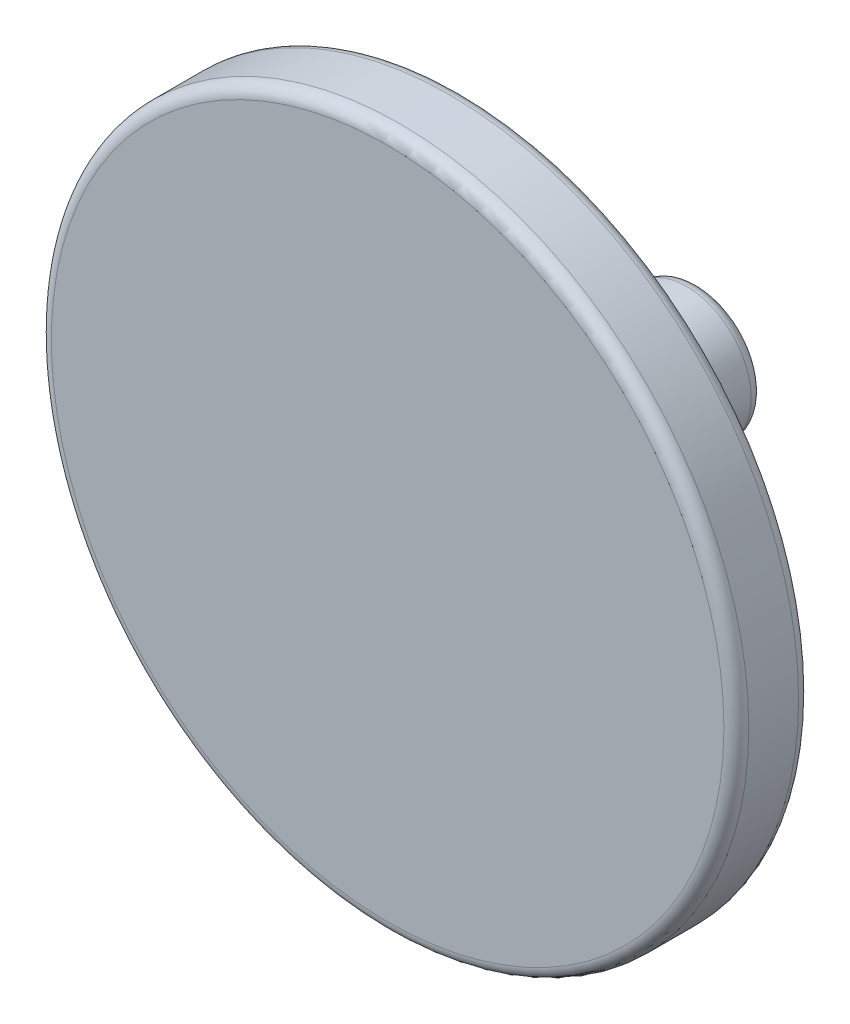
SolidWorks part; units mm, degrees
ref_plane "Front Plane" through (0, 0, 0) normal (0, 0, 1) x (1, 0, 0)
ref_plane "Top Plane" through (0, 0, 0) normal (0, 1, 0) x (1, 0, 0)
ref_plane "Right Plane" through (0, 0, 0) normal (1, 0, 0) x (0, 0, -1)
sketch "Sketch1" plane through (0, 0, 0) normal (0, 0, 1) x (1, 0, 0)
  circle A0 centre (17.35, 0) radius 3.25
  dimension "D1" = 6.5
extrude "Boss-Extrude1" add sketch "Sketch1" along normal blind 2 and the other way blind 3
sketch "Sketch2" plane through (0, 0, 2) normal (0, 0, 1) x (1, 0, 0)
  circle A0 centre (17.35, 0) radius 14
  dimension "D1" = 28
extrude "Boss-Extrude2" add sketch "Sketch2" along normal blind 3
sketch "Sketch3" plane through (0, 0, -3) normal (0, 0, -1) x (-1, 0, 0)
  circle A0 centre (-17.35, 0) radius 2.6
  dimension "D1" = 5.2
extrude "Boss-Extrude3" add sketch "Sketch3" along normal blind 4.5
fillet "Fillet1" radius 0.5 4 edges at (20.6, 0, 2) (31.35, 0, 5) (31.35, 0, 2) (14.75, 0, -7.5)
